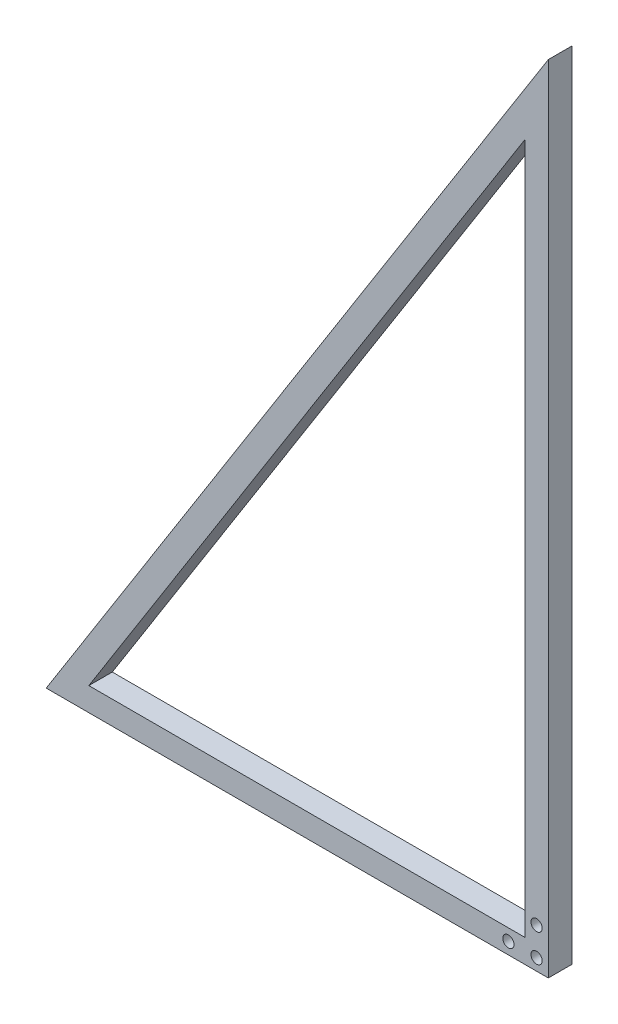
SolidWorks part; units mm, degrees
ref_plane "Alzado" through (0, 0, 0) normal (0, 0, 1) x (1, 0, 0)
ref_plane "Planta" through (0, 0, 0) normal (0, 1, 0) x (1, 0, 0)
ref_plane "Vista lateral" through (0, 0, 0) normal (1, 0, 0) x (0, 0, -1)
sketch "Croquis1" plane through (0, 0, 0) normal (0, 0, 1) x (1, 0, 0)
  line L0 (0, -55) -> (0, 55) construction
  line L1 (-3.125, 100) -> (3.125, 100)
  line L2 (-3.125, 100) -> (-3.125, -100)
  line L3 (-3.125, -100) -> (3.125, -100)
  line L4 (3.125, 100) -> (3.125, -100)
  line L5 (55, 0) -> (-55, 0) construction
  point P4 (0, 100)
  point P5 (-3.125, 0)
  dimension "D1" = 6.25
  dimension "D2" = 200
extrude "Saliente-Extruir1" add sketch "Croquis1" along normal mid plane 6.25
sketch "Croquis3" plane through (0, 0, 3.125) normal (0, 0, 1) x (1, 0, 0)
  line L0 (3.125, 100) -> (-3.125, 93.75)
  line L1 (-3.125, 100) -> (-3.125, -100) construction
  line L2 (-3.125, 93.75) -> (-3.125, 100)
  line L3 (-3.125, 100) -> (3.125, 100)
  dimension "D1" = 45
extrude "Cortar-Extruir1" cut sketch "Croquis3" against normal blind 6.25
sketch "Croquis4" plane through (0, 0, 3.125) normal (0, 0, 1) x (1, 0, 0)
  line L0 (-3.125, -100) -> (-123.125, -100)
  line L1 (-123.125, -100) -> (-123.125, -93.75)
  line L2 (-123.125, -93.75) -> (-3.125, -93.75)
  line L3 (-3.125, 93.75) -> (-3.125, -100) construction
  line L4 (-3.125, -93.75) -> (-3.125, -100)
  dimension "D1" = 6.25
  dimension "D2" = 120
extrude "Saliente-Extruir2" add sketch "Croquis4" against normal blind 6.25
sketch "Croquis7" plane through (0, 0, 3.125) normal (0, 0, 1) x (1, 0, 0)
  line L0 (-123.125, -100) -> (3.125, 100)
  line L1 (3.125, 100) -> (-2.1601, 103.3362)
  line L2 (-2.1601, 103.3362) -> (-130.5161, -100)
  line L3 (-130.5161, -100) -> (-123.125, -100)
  dimension "D1" = 6.25
extrude "Saliente-Extruir3" add sketch "Croquis7" against normal blind 6.25
sketch "Croquis9" plane through (0, 0, 3.125) normal (0, 0, 1) x (1, 0, 0)
  line L0 (3.125, 100) -> (-2.1601, 103.3362)
  line L1 (-2.1601, 103.3362) -> (3.125, 111.7086)
  line L2 (3.125, 111.7086) -> (3.125, 100)
extrude "Saliente-Extruir4" add sketch "Croquis9" against normal blind 6.25
sketch "Croquis10" plane through (0, 0, 3.125) normal (0, 0, 1) x (1, 0, 0)
  line L0 (-130.5161, -100) -> (3.125, -100) construction
  line L1 (3.125, -100) -> (3.125, 111.7086) construction
  line L2 (0, -96.875) -> (-12.5685, -96.875) construction
  line L3 (0, -3.4376) -> (0, 3.4376) construction
  line L4 (-3.125, 90.099) -> (-3.125, -93.75) construction
  circle A0 centre (0, -96.875) radius 1.5
  circle A1 centre (0, -89.375) radius 1.5
  circle A2 centre (-7.5, -96.875) radius 1.5
  point P0 (0, -96.875)
  point P7 (-7.5, -96.875)
  point P9 (0, -89.375)
  dimension "D3" = 7.5
  dimension "D4" = 4.375
  dimension "D1" = 3.125
  dimension "D2" = 3.125
extrude "Cortar-Extruir3" cut sketch "Croquis10" against normal blind 16.25
